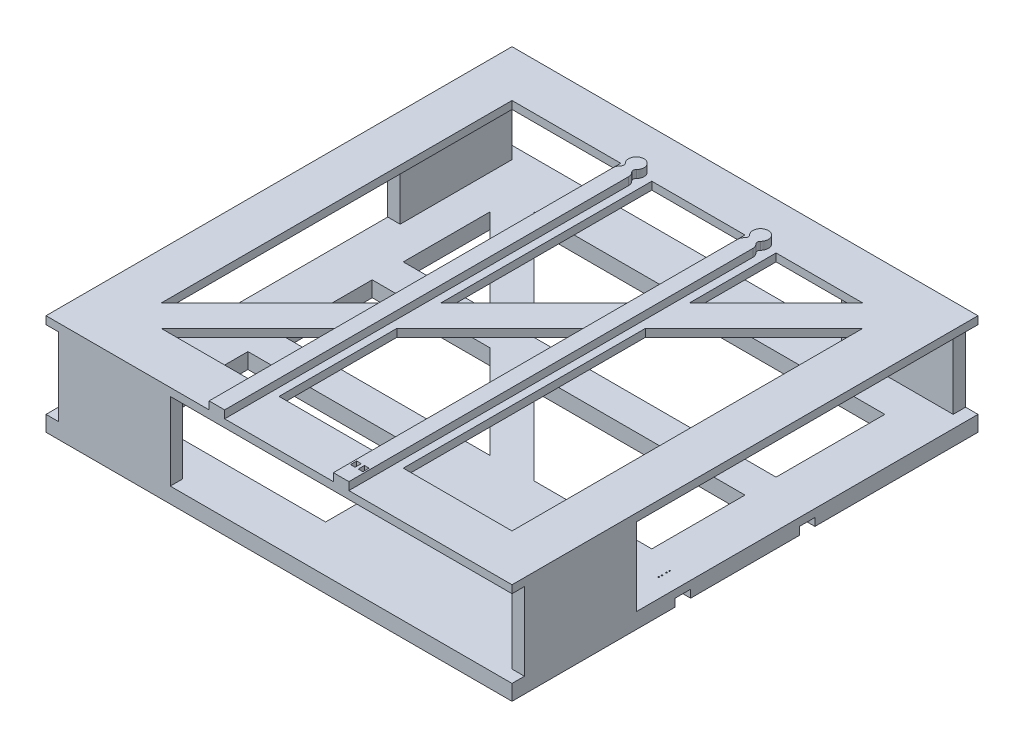
SolidWorks part; units mm, degrees
other "相机1"
material "3.0526 (EN-AW 3005)"
ref_plane "前视基准面" through (0, 0, 0) normal (0, 0, 1) x (1, 0, 0)
ref_plane "上视基准面" through (0, 0, 0) normal (0, 1, 0) x (1, 0, 0)
ref_plane "右视基准面" through (0, 0, 0) normal (1, 0, 0) x (0, 0, -1)
sketch "草图1" plane through (0, 0, 0) normal (0, 1, 0) x (1, 0, 0)
  line L0 (-15.8579, 30) -> (120, 30)
  line L1 (-150, 150) -> (150, 150)
  line L2 (-150, 150) -> (-150, -150)
  line L3 (-150, -150) -> (0, -150)
  line L4 (150, 150) -> (150, -30)
  line L5 (-105.8579, 120) -> (120, 120)
  line L6 (-120, 105.8579) -> (-120, 50)
  line L7 (-120, -120) -> (0, -120)
  line L8 (120, 120) -> (120, 50)
  line L9 (150, -150) -> (0, -150)
  line L10 (150, -150) -> (150, -30)
  line L11 (120, 30) -> (120, -30)
  line L12 (0, -120) -> (0, -50)
  line L13 (-120, 105.8579) -> (-64.1421, 50)
  line L14 (-105.8579, 120) -> (-35.8579, 50)
  line L16 (-120, -50) -> (-120, -120)
  line L17 (-120, 30) -> (-44.1421, 30)
  line L18 (-120, 50) -> (-64.1421, 50)
  line L19 (-120, -50) -> (0, -50)
  line L20 (-120, -30) -> (15.8579, -30)
  line L21 (-120, 30) -> (-120, -30)
  line L22 (44.1421, -30) -> (120, -30)
  line L26 (-44.1421, 30) -> (15.8579, -30)
  line L27 (-15.8579, 30) -> (44.1421, -30)
  line L28 (-35.8579, 50) -> (120, 50)
  point P4 (-120, 120)
  point P5 (120, -120)
  point P11 (-127.0711, 112.9289)
  point P12 (112.9289, -127.0711)
  point P13 (-112.9289, 127.0711)
  point P14 (127.0711, -112.9289)
  point P15 (-120, 40)
  point P16 (120, 40)
  point P17 (-120, -40)
  point P18 (120, -40)
  point P24 (120, -50)
extrude "凸台-拉伸1" add sketch "草图1" along normal blind 5
sketch "草图2" plane through (0, 0, 0) normal (0, -1, 0) x (1, 0, 0)
  line L0 (150, 45) -> (150, 150)
  line L5 (-110, -45) -> (150, -45)
  line L6 (-110, 35) -> (150, 35)
  line L7 (-110, -35) -> (150, -35)
  line L8 (-110, 45) -> (150, 45)
  line L9 (150, 150) -> (-150, 150)
  line L10 (-150, 150) -> (-150, -150)
  line L11 (-150, -150) -> (150, -150)
  line L12 (150, -150) -> (150, -45)
  line L13 (150, -35) -> (150, 35)
  line L14 (-120, 120) -> (-120, 50)
  line L15 (-120, 50) -> (0, 50)
  line L16 (0, 50) -> (0, 120)
  line L17 (0, 120) -> (-120, 120)
  line L18 (-120, 30) -> (-120, -30)
  line L19 (-120, -30) -> (-44.1421, -30)
  line L20 (-44.1421, -30) -> (15.8579, 30)
  line L21 (15.8579, 30) -> (-120, 30)
  line L22 (44.1421, 30) -> (-15.8579, -30)
  line L23 (-15.8579, -30) -> (120, -30)
  line L24 (120, -30) -> (120, 30)
  line L25 (120, 30) -> (44.1421, 30)
  line L26 (-120, -50) -> (-120, -105.8579)
  line L27 (-120, -105.8579) -> (-64.1421, -50)
  line L28 (-64.1421, -50) -> (-120, -50)
  line L29 (-35.8579, -50) -> (-105.8579, -120)
  line L30 (-105.8579, -120) -> (120, -120)
  line L31 (120, -120) -> (120, -50)
  line L32 (120, -50) -> (-35.8579, -50)
  arc A0 (-116.4645, 43.5355) -> (-116.4645, 36.4645) centre (-120, 40) ccw
  arc A1 (-116.4645, 43.5355) -> (-113.5355, 43.5355) centre (-115, 45) ccw
  arc A2 (-113.5355, 36.4645) -> (-116.4645, 36.4645) centre (-115, 35) ccw
  arc A3 (-110, 35) -> (-113.5355, 36.4645) centre (-110, 40) cw
  arc A4 (-113.5355, 43.5355) -> (-110, 45) centre (-110, 40) cw
  arc A5 (-113.5355, -43.5355) -> (-110, -45) centre (-110, -40) ccw
  arc A6 (-116.4645, -43.5355) -> (-113.5355, -43.5355) centre (-115, -45) cw
  arc A7 (-116.4645, -43.5355) -> (-116.4645, -36.4645) centre (-120, -40) cw
  arc A8 (-113.5355, -36.4645) -> (-116.4645, -36.4645) centre (-115, -35) cw
  arc A9 (-110, -35) -> (-113.5355, -36.4645) centre (-110, -40) ccw
  point P5 (-150, 40)
  point P8 (150, 40)
  point P11 (-120, 35)
  point P14 (-120, 45)
extrude "凸台-拉伸2" add sketch "草图2" along normal blind 5
sketch "草图3" plane through (0, 5, 0) normal (0, 1, 0) x (1, 0, 0)
  line L0 (142, -142) -> (150, -142)
  line L1 (-142, -142) -> (-70, -142)
  line L2 (150, -142) -> (150, -70)
  line L3 (150, -70) -> (142, -70)
  line L4 (142, -142) -> (142, -70)
  line L5 (-70, -150) -> (-70, -142)
  line L6 (-142, -142) -> (-142, -150)
  line L7 (-142, -150) -> (-70, -150)
  line L8 (-142, 142) -> (-142, 70)
  line L9 (-150, 70) -> (-142, 70)
  line L10 (-142, 142) -> (-150, 142)
  line L11 (-150, 142) -> (-150, 70)
  line L12 (142, 142) -> (70, 142)
  line L13 (70, 150) -> (70, 142)
  line L14 (142, 142) -> (142, 150)
  line L15 (142, 150) -> (70, 150)
  point P19 (0, 0)
  dimension "D1" = 4
extrude "凸台-拉伸3" add sketch "草图3" along normal blind 50
sketch "草图4" plane through (0, 55, 0) normal (0, 1, 0) x (1, 0, 0)
  line L0 (30, 120) -> (-30, 120)
  line L1 (-150, 150) -> (150, 150)
  line L2 (-150, 150) -> (-150, -150)
  line L3 (-150, -150) -> (150, -150)
  line L4 (150, 150) -> (150, -150)
  line L5 (105.8579, 120) -> (50, 120)
  line L6 (120, 105.8579) -> (120, -120)
  line L7 (120, -120) -> (50, -120)
  line L8 (-120, 120) -> (-120, -105.8579)
  line L9 (105.8579, 120) -> (50, 64.1421)
  line L10 (120, 105.8579) -> (50, 35.8579)
  line L11 (-50, -120) -> (-105.8579, -120)
  line L12 (30, -120) -> (-30, -120)
  line L13 (-50, 120) -> (-50, -35.8579)
  line L14 (-30, 120) -> (-30, -15.8579)
  line L15 (30, 120) -> (30, 44.1421)
  line L16 (50, 120) -> (50, 64.1421)
  line L17 (-50, 120) -> (-120, 120)
  line L18 (-50, -35.8579) -> (-120, -105.8579)
  line L19 (-30, -44.1421) -> (-30, -120)
  line L20 (-50, -64.1421) -> (-105.8579, -120)
  line L22 (-50, -64.1421) -> (-50, -120)
  line L24 (30, 15.8579) -> (30, -120)
  line L25 (30, 44.1421) -> (-30, -15.8579)
  line L27 (50, 35.8579) -> (50, -120)
  line L28 (30, 15.8579) -> (-30, -44.1421)
  point P6 (120, 120)
  point P7 (-120, -120)
  point P12 (112.9289, 127.0711)
  point P13 (-127.0711, -112.9289)
  point P14 (127.0711, 112.9289)
  point P15 (-112.9289, -127.0711)
  point P16 (-40, 120)
  point P17 (-40, -120)
  point P18 (40, 120)
  point P19 (40, -120)
extrude "凸台-拉伸4" add sketch "草图4" along normal blind 5
sketch "草图5" plane through (0, 60, 0) normal (0, 1, 0) x (1, 0, 0)
  line L0 (35, 110) -> (35, -150)
  line L1 (-45, -150) -> (-35, -150)
  line L2 (45, 110) -> (45, -150)
  line L4 (35, -150) -> (45, -150)
  line L5 (-45, 110) -> (-45, -150)
  line L6 (-35, 110) -> (-35, -150)
  arc A0 (-36.4645, 116.4645) -> (-43.5355, 116.4645) centre (-40, 120) ccw
  arc A1 (-36.4645, 116.4645) -> (-36.4645, 113.5355) centre (-35, 115) ccw
  arc A2 (-43.5355, 113.5355) -> (-43.5355, 116.4645) centre (-45, 115) ccw
  arc A3 (43.5355, 116.4645) -> (36.4645, 116.4645) centre (40, 120) ccw
  arc A4 (43.5355, 116.4645) -> (43.5355, 113.5355) centre (45, 115) ccw
  arc A5 (36.4645, 113.5355) -> (36.4645, 116.4645) centre (35, 115) ccw
  arc A6 (-36.4645, 113.5355) -> (-35, 110) centre (-40, 110) cw
  arc A7 (43.5355, 113.5355) -> (45, 110) centre (40, 110) cw
  arc A8 (-45, 110) -> (-43.5355, 113.5355) centre (-40, 110) cw
  arc A9 (35, 110) -> (36.4645, 113.5355) centre (40, 110) cw
  point P9 (-40, -150)
  point P14 (-45, 120)
  point P16 (-35, 120)
  point P18 (35, 120)
  point P20 (45, 120)
extrude "凸台-拉伸5" add sketch "草图5" along normal blind 5
sketch "草图6" plane through (0, 0, 0) normal (0, -1, 0) x (1, 0, 0)
  line L1 (140, 44) -> (136, 44)
  line L2 (140, 44) -> (140, 41)
  line L3 (140, 36) -> (136, 36)
  line L4 (136, 44) -> (136, 41)
  line L7 (136, 39) -> (140, 39)
  line L8 (136, 41) -> (140, 41)
  line L9 (136, 39) -> (136, 36)
  line L10 (140, 39) -> (140, 36)
extrude "切除-拉伸1" cut sketch "草图6" against normal blind 3
sketch "草图7" plane through (0, 3, 0) normal (0, -1, 0) x (1, 0, 0)
  circle A0 centre (138, 43.5) radius 0.4
  circle A1 centre (138, 41.5) radius 0.4
  circle A2 centre (138, 36.5) radius 0.4
  circle A3 centre (138, 38.5) radius 0.4
extrude "切除-拉伸2" cut sketch "草图7" against normal blind 3
sketch "草图8" plane through (0, 65, 0) normal (0, 1, 0) x (1, 0, 0)
  line L0 (39, -136) -> (36, -136)
  line L1 (44, -140) -> (41, -140)
  line L2 (44, -140) -> (44, -136)
  line L3 (44, -136) -> (41, -136)
  line L4 (36, -140) -> (36, -136)
  line L5 (39, -136) -> (39, -140)
  line L6 (41, -136) -> (41, -140)
  line L7 (39, -140) -> (36, -140)
extrude "切除-拉伸3" cut sketch "草图8" against normal blind 3
sketch "草图9" plane through (0, 62, 0) normal (0, 1, 0) x (1, 0, 0)
  circle A0 centre (43.5, -138) radius 0.4
  circle A1 centre (41.5, -138) radius 0.4
  circle A2 centre (36.5, -138) radius 0.4
  circle A3 centre (38.5, -138) radius 0.4
extrude "切除-拉伸4" cut sketch "草图9" against normal blind 3
